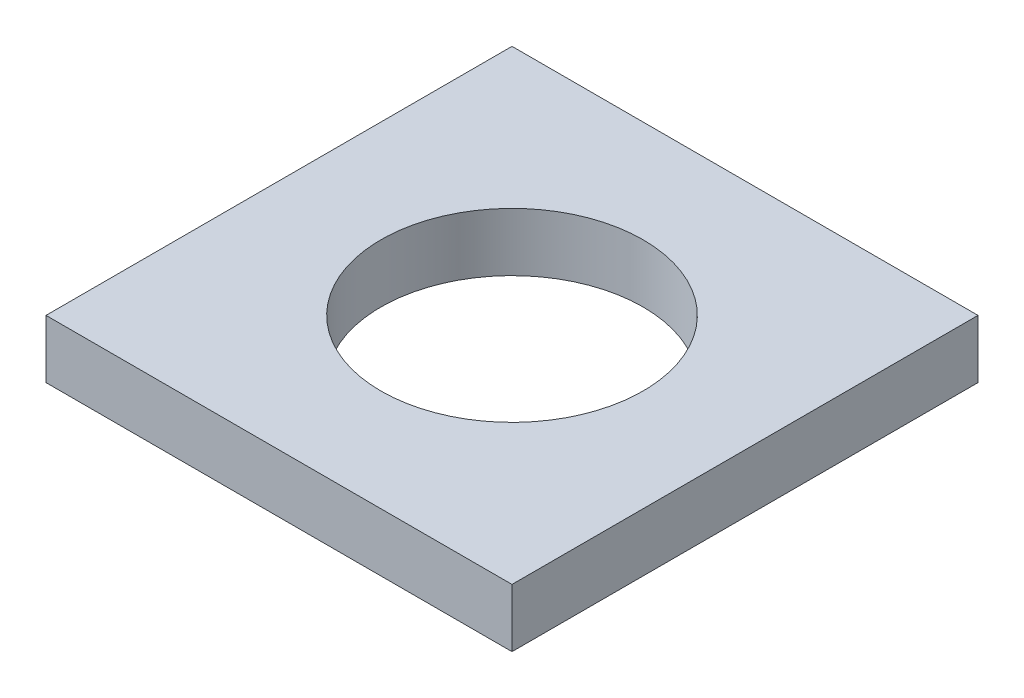
SolidWorks part; units mm, degrees
ref_plane "Alzado" through (0, 0, 0) normal (0, 0, 1) x (1, 0, 0)
ref_plane "Planta" through (0, 0, 0) normal (0, 1, 0) x (1, 0, 0)
ref_plane "Vista lateral" through (0, 0, 0) normal (1, 0, 0) x (0, 0, -1)
sketch "Croquis1" plane through (0, 0, 0) normal (0, 1, 0) x (1, 0, 0)
  line L1 (0, 0) -> (101.6, 0)
  line L2 (0, 0) -> (0, 101.6)
  line L3 (0, 101.6) -> (101.6, 101.6)
  line L4 (101.6, 0) -> (101.6, 101.6)
  dimension "D1" = 101.6
  dimension "D2" = 101.6
extrude "Saliente-Extruir1" add sketch "Croquis1" along normal blind 12.7
sketch "Croquis2" plane through (0, 0, 0) normal (0, -1, 0) x (1, 0, 0)
  line L0 (101.6, -50.8) -> (0, -50.8) construction
  line L1 (101.6, 0) -> (101.6, -101.6) construction
  line L2 (0, -101.6) -> (0, 0) construction
  circle A0 centre (50.8, -50.8) radius 28.575
  dimension "D1" = 57.15
extrude "Cortar-Extruir1" cut sketch "Croquis2" against normal blind 12.7
